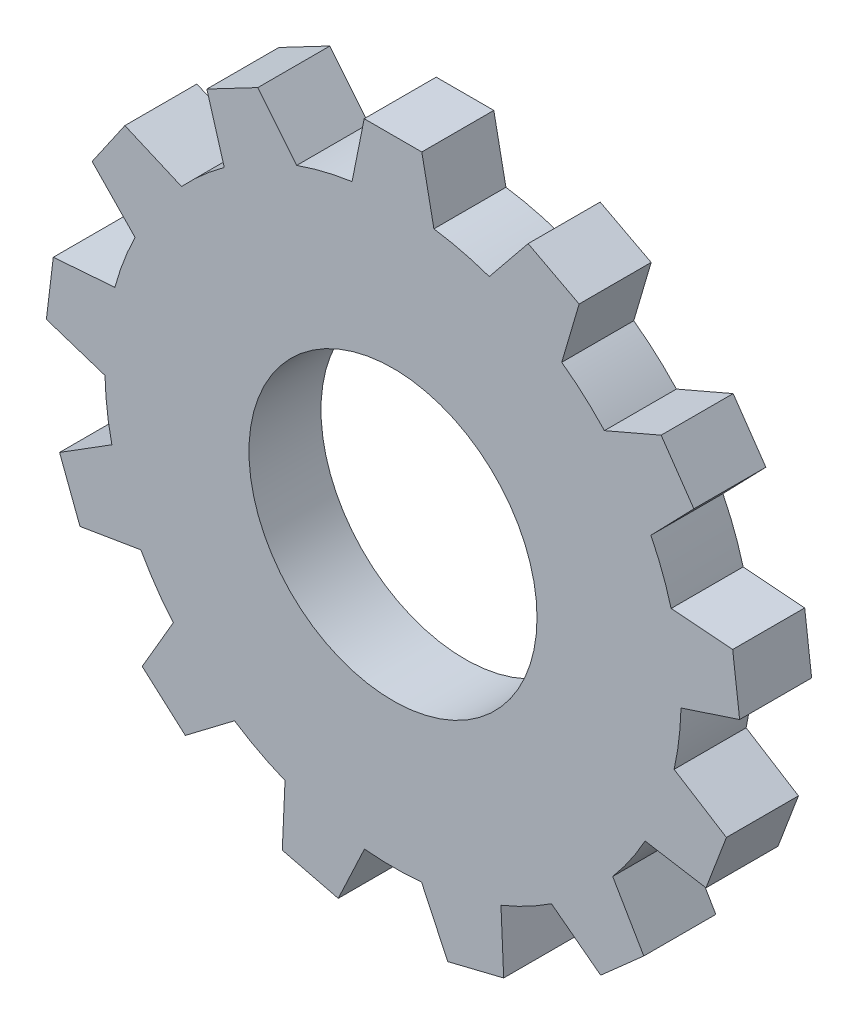
SolidWorks part; units mm, degrees
ref_plane "Front Plane" through (0, 0, 0) normal (0, 0, 1) x (1, 0, 0)
ref_plane "Top Plane" through (0, 0, 0) normal (0, 1, 0) x (1, 0, 0)
ref_plane "Right Plane" through (0, 0, 0) normal (1, 0, 0) x (0, 0, -1)
sketch "Sketch1" plane through (0, 0, 0) normal (0, 0, 1) x (1, 0, 0)
  circle A1 centre (0, 0) radius 12.7
  circle A2 centre (0, 0) radius 6.35
  dimension "D1" = 25.4
  dimension "D3" = 12.7
extrude "Boss-Extrude1" add sketch "Sketch1" along normal blind 3.175
sketch "Sketch2" plane through (0, 0, 0) normal (0, 0, 1) x (1, 0, 0)
  line L0 (-1.27, 15.24) -> (1.27, 15.24)
  line L1 (1.27, 15.24) -> (1.905, 12.065)
  line L2 (1.905, 12.065) -> (-1.905, 12.065)
  line L3 (-1.905, 12.065) -> (-1.27, 15.24)
  point P2 (0, 15.24)
  point P6 (0, 12.065)
  point P7 (0, 0)
  point P8 (0, 0)
  dimension "D1" = 15.24
  dimension "D2" = 3.175
  dimension "D3" = 2.54
  dimension "D4" = 3.81
extrude "Boss-Extrude2" add sketch "Sketch2" along normal blind 3.175
pattern_circular "CirPattern1" count 13 over 360 about axis through (0, 0, 0) along (0, 0, 1) of "Boss-Extrude2"
